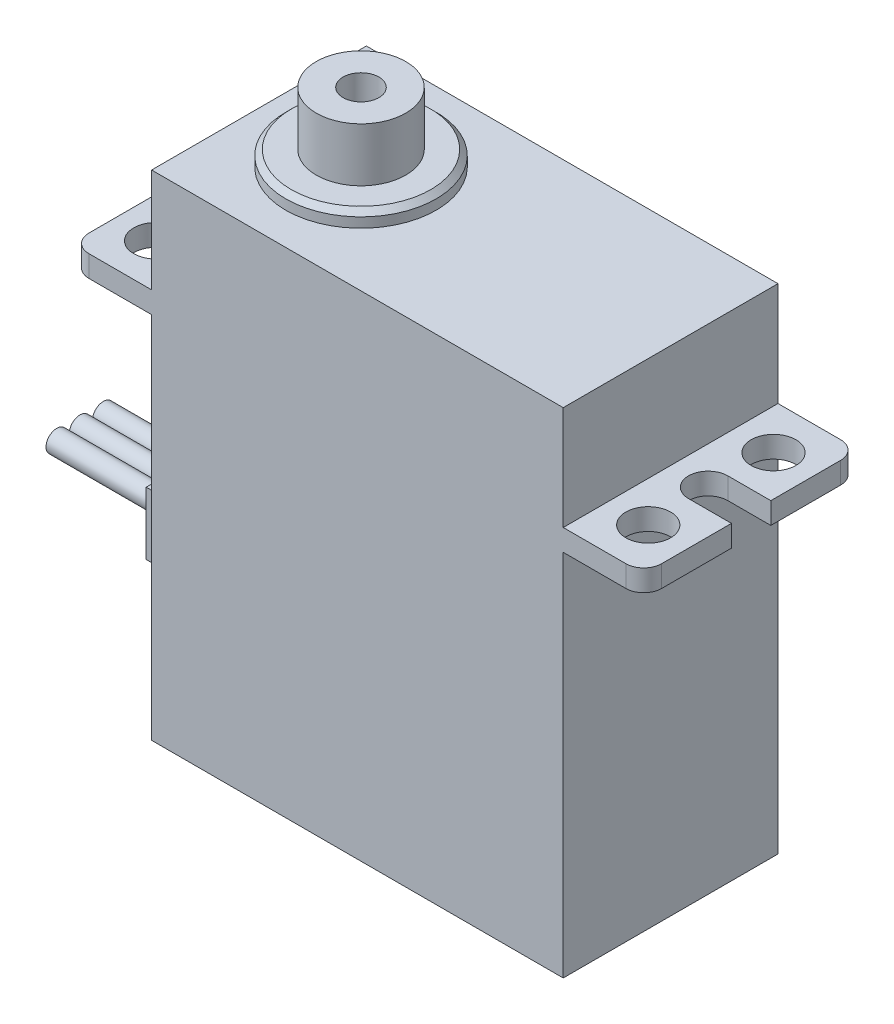
SolidWorks part; units mm, degrees
ref_plane "Front Plane" through (0, 0, 0) normal (0, 0, 1) x (1, 0, 0)
ref_plane "Top Plane" through (0, 0, 0) normal (0, 1, 0) x (1, 0, 0)
ref_plane "Right Plane" through (0, 0, 0) normal (1, 0, 0) x (0, 0, -1)
sketch "Эскиз1" plane through (0, 0, 0) normal (0, 0, 1) x (1, 0, 0)
  line L0 (0, 5.0732) -> (0, -2.902) construction
  line L1 (-11.5, -13.8) -> (11.5, -13.8)
  line L2 (-11.5, -13.8) -> (-11.5, 13.8)
  line L3 (-11.5, 13.8) -> (11.5, 13.8)
  line L4 (11.5, -13.8) -> (11.5, 13.8)
  line L5 (-11.5, -13.8) -> (11.5, 13.8) construction
  line L6 (-11.5, 13.8) -> (11.5, -13.8) construction
  line L7 (-16, 6.8) -> (-11.5, 6.8)
  line L8 (-16, 6.8) -> (-16, 8)
  line L9 (-16, 8) -> (-11.5, 8)
  line L10 (-11.5, 6.8) -> (-11.5, 8)
  line L11 (-16, 6.8) -> (-11.5, 8) construction
  line L12 (-16, 8) -> (-11.5, 6.8) construction
  line L13 (16, 8) -> (11.5, 8)
  line L14 (11.5, 6.8) -> (11.5, 8)
  line L15 (16, 6.8) -> (11.5, 6.8)
  line L16 (16, 6.8) -> (16, 8)
  point P0 (0, 0)
  point P5 (-13.75, 7.4)
  dimension "D1" = 23
  dimension "D2" = 27.6
  dimension "D3" = 20.6
  dimension "D4" = 1.2
  dimension "D5" = 32
extrude "Бобышка-Вытянуть1" add sketch "Эскиз1" along normal mid plane 12 contours L1 L4 L3 L2 | L9 L8 L7 L2 | L15 L16 L13 L4
sketch "Эскиз2" plane through (0, 13.8, 0) normal (0, 1, 0) x (1, 0, 0)
  line L0 (-11.5, 0) -> (11.5, 0) construction
  line L1 (-11.5, -6) -> (-11.5, 6) construction
  line L2 (11.5, -6) -> (11.5, 6) construction
  line L3 (-11.5, -6) -> (-11.5, 6) construction
  circle A0 centre (-5.8, 0) radius 4.2
  dimension "D1" = 8.4
  dimension "D2" = 1.5
extrude "Бобышка-Вытянуть2" add sketch "Эскиз2" along normal blind 0.85
chamfer "Фаска1" distance 0.3 angle 45 1 edges at (-5.8, 14.65, 4.2)
sketch "Эскиз4" plane through (0, 14.65, 0) normal (0, 1, 0) x (1, 0, 0)
  circle A0 centre (-5.8, 0) radius 2.5
  circle A1 centre (-5.8, 0) radius 3.9
  circle A2 centre (-5.8, 0) radius 3.9 construction
  circle A3 centre (-5.8, 0) radius 1
  dimension "D2" = 5
  dimension "D3" = 2
  dimension "D1" = 0
extrude "Бобышка-Вытянуть3" add sketch "Эскиз4" along normal blind 3
sketch "Эскиз3" plane through (0, 8, 0) normal (0, 1, 0) x (1, 0, 0)
  line L0 (-13.75, 6) -> (-13.75, -6) construction
  line L1 (-16, 6) -> (-11.5, 6) construction
  line L2 (-16, -6) -> (-11.5, -6) construction
  line L3 (0, -6) -> (0, 6) construction
  line L4 (-11.5, -6) -> (11.5, -6) construction
  line L5 (-11.5, 6) -> (11.5, 6) construction
  line L6 (-16, 0) -> (16, 0) construction
  line L7 (-16, -6) -> (-16, 6) construction
  line L8 (16, -6) -> (16, 6) construction
  line L9 (-16, 1.1) -> (-13.6, 1.1)
  line L10 (-13.6, -1.1) -> (-16, -1.1)
  line L11 (-12.5, 4.2867) -> (-12.5, 2.4321) construction
  line L12 (-16, 1.1) -> (-16, -1.1)
  line L13 (16, 1.1) -> (13.6, 1.1)
  line L14 (13.6, -1.1) -> (16, -1.1)
  line L15 (16, 1.1) -> (16, -1.1)
  circle A0 centre (-13.75, 3.5) radius 1.25
  circle A1 centre (-13.75, -3.5) radius 1.25
  circle A2 centre (13.75, -3.5) radius 1.25
  circle A3 centre (13.75, 3.5) radius 1.25
  arc A4 (-13.6, 1.1) -> (-13.6, -1.1) centre (-13.6, 0) cw
  arc A5 (13.6, 1.1) -> (13.6, -1.1) centre (13.6, 0) ccw
  dimension "D1" = 2.5
  dimension "D2" = 7
  dimension "D3" = 12
  dimension "D4" = 2.5
  dimension "D5" = 2.2
  dimension "D6" = 1.1
extrude "Вырез-Вытянуть1" cut sketch "Эскиз3" against normal through all both and the other way through all
fillet "Скругление1" radius 1 4 edges at (-16, 7.4, -6) (16, 7.4, -6) (16, 7.4, 6) (-16, 7.4, 6)
sketch "Эскиз5" plane through (-11.5, 0, 0) normal (-1, 0, 0) x (0, 0, 1)
  line L0 (0, -13.8) -> (0, 0) construction
  line L1 (6, -13.8) -> (-6, -13.8) construction
  line L2 (-6, -6.65) -> (6, -6.65) construction
  line L3 (-6, -13.8) -> (-6, 6.8) construction
  line L4 (6, -13.8) -> (6, 6.8) construction
  line L6 (-2.8, -8.4) -> (2.8, -8.4)
  line L7 (-2.8, -8.4) -> (-2.8, -4.9)
  line L8 (-2.8, -4.9) -> (2.8, -4.9)
  line L9 (2.8, -8.4) -> (2.8, -4.9)
  line L10 (-2.8, -8.4) -> (2.8, -4.9) construction
  line L11 (-2.8, -4.9) -> (2.8, -8.4) construction
  point P11 (0, -6.65)
  dimension "D1" = 5.4
  dimension "D2" = 3.5
  dimension "D3" = 5.6
extrude "Бобышка-Вытянуть4" add sketch "Эскиз5" along normal blind 3.5
sketch "Эскиз6" plane through (-15, 0, 0) normal (-1, 0, 0) x (0, 0, 1)
  line L0 (-2.8, -6.65) -> (2.8, -6.65) construction
  line L1 (0, -4.9) -> (0, -8.4) construction
  line L4 (2.8, -8.4) -> (2.8, -4.9)
  line L5 (2.8, -4.9) -> (-2.8, -4.9)
  line L6 (-2.8, -4.9) -> (-2.8, -8.4)
  line L7 (-2.8, -8.4) -> (2.8, -8.4)
  line L8 (2.8, -8.4) -> (2.8, -4.9) construction
  line L9 (2.8, -4.9) -> (-2.8, -4.9) construction
  line L10 (-2.8, -4.9) -> (-2.8, -8.4) construction
  line L11 (-2.8, -8.4) -> (2.8, -8.4) construction
  circle A0 centre (0, -6.65) radius 0.6
  circle A1 centre (1.3, -6.65) radius 0.6
  circle A2 centre (-1.3, -6.65) radius 0.6
  dimension "D2" = 1.2
  dimension "D3" = 0.1
  dimension "D4" = 0.1
  dimension "D1" = 0
extrude "Бобышка-Вытянуть7" add sketch "Эскиз6" along normal blind 6.5
equation "\"D4@Эскиз3\"=\"D3@Эскиз3\"/2 - \"D2@Эскиз3\"/2"
equation "\"D6@Эскиз3\"=\"D5@Эскиз3\"/2"
